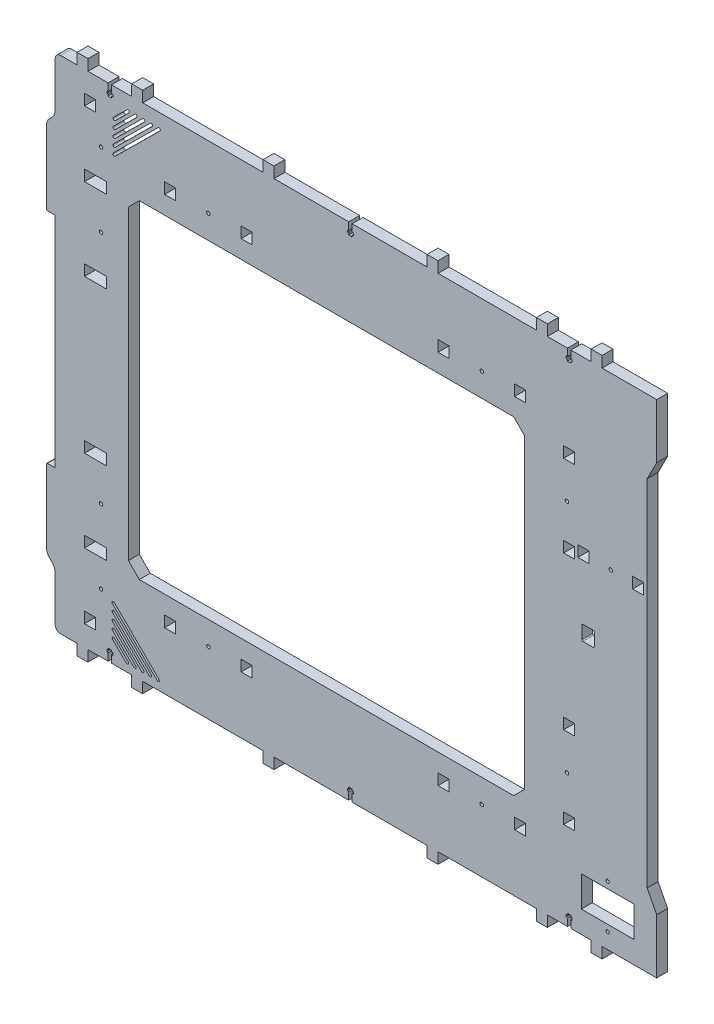
SolidWorks part; units mm, degrees
ref_plane "Front" through (0, 0, 0) normal (0, 0, 1) x (1, 0, 0)
ref_plane "Top" through (0, 0, 0) normal (0, 1, 0) x (1, 0, 0)
ref_plane "Right" through (0, 0, 0) normal (1, 0, 0) x (0, 0, -1)
sketch "Эскиз1" plane through (0, 0, 0) normal (0, 0, 1) x (1, 0, 0)
  line L256 (-788.0021, 303.5227) -> (-779.3021, 286.5227)
  line L257 (-788.0021, 627.5227) -> (-788.0021, 303.5227)
  line L258 (-779.3021, 644.5227) -> (-788.0021, 627.5227)
  line L259 (-779.3021, 694.5227) -> (-779.3021, 644.5227)
  line L260 (-829.2021, 694.5227) -> (-779.3021, 694.5227)
  line L261 (-829.2355, 704.5213) -> (-829.2021, 694.5227)
  line L262 (-839.2355, 704.5213) -> (-829.2355, 704.5213)
  line L263 (-839.4021, 694.5227) -> (-839.2355, 704.5213)
  line L264 (-857.7521, 694.5227) -> (-839.4021, 694.5227)
  line L265 (-857.7521, 687.7227) -> (-857.7521, 694.5227)
  line L266 (-856.5521, 687.7227) -> (-857.7521, 687.7227)
  line L267 (-856.5521, 685.5227) -> (-856.5521, 687.7227)
  line L268 (-857.7521, 685.5227) -> (-856.5521, 685.5227)
  line L269 (-857.7521, 684.0227) -> (-857.7521, 685.5227)
  line L270 (-860.8521, 684.0227) -> (-857.7521, 684.0227)
  line L271 (-860.8521, 685.5227) -> (-860.8521, 684.0227)
  line L272 (-862.0521, 685.5227) -> (-860.8521, 685.5227)
  line L273 (-862.0521, 687.7227) -> (-862.0521, 685.5227)
  line L274 (-860.8521, 687.7227) -> (-862.0521, 687.7227)
  line L275 (-860.8521, 694.5227) -> (-860.8521, 687.7227)
  line L276 (-879.2021, 694.5227) -> (-860.8521, 694.5227)
  line L277 (-879.2355, 704.5213) -> (-879.2021, 694.5227)
  line L278 (-889.2355, 704.5213) -> (-879.2355, 704.5213)
  line L279 (-889.4021, 694.5227) -> (-889.2355, 704.5213)
  line L280 (-979.2021, 694.5227) -> (-889.4021, 694.5227)
  line L281 (-979.2355, 704.5213) -> (-979.2021, 694.5227)
  line L282 (-989.2355, 704.5213) -> (-979.2355, 704.5213)
  line L283 (-989.4021, 694.5227) -> (-989.2355, 704.5213)
  line L284 (-1057.7521, 694.5227) -> (-989.4021, 694.5227)
  line L285 (-1057.7521, 687.7227) -> (-1057.7521, 694.5227)
  line L286 (-1056.5521, 687.7227) -> (-1057.7521, 687.7227)
  line L287 (-1056.5521, 685.5227) -> (-1056.5521, 687.7227)
  line L288 (-1057.7521, 685.5227) -> (-1056.5521, 685.5227)
  line L289 (-1057.7521, 684.0227) -> (-1057.7521, 685.5227)
  line L290 (-1060.8521, 684.0227) -> (-1057.7521, 684.0227)
  line L291 (-1060.8521, 685.5227) -> (-1060.8521, 684.0227)
  line L292 (-1062.0521, 685.5227) -> (-1060.8521, 685.5227)
  line L293 (-1062.0521, 687.7227) -> (-1062.0521, 685.5227)
  line L294 (-1060.8521, 687.7227) -> (-1062.0521, 687.7227)
  line L295 (-1060.8521, 694.5227) -> (-1060.8521, 687.7227)
  line L296 (-1129.2021, 694.5227) -> (-1060.8521, 694.5227)
  line L297 (-1129.2355, 704.5213) -> (-1129.2021, 694.5227)
  line L298 (-1139.2355, 704.5213) -> (-1129.2355, 704.5213)
  line L299 (-1139.4021, 694.5227) -> (-1139.2355, 704.5213)
  line L300 (-1249.2021, 694.5227) -> (-1139.4021, 694.5227)
  line L301 (-1249.2355, 704.5213) -> (-1249.2021, 694.5227)
  line L302 (-1259.2355, 704.5213) -> (-1249.2355, 704.5213)
  line L303 (-1259.4021, 694.5227) -> (-1259.2355, 704.5213)
  line L304 (-1277.7521, 694.5227) -> (-1259.4021, 694.5227)
  line L305 (-1277.7521, 687.7227) -> (-1277.7521, 694.5227)
  line L306 (-1276.5521, 687.7227) -> (-1277.7521, 687.7227)
  line L307 (-1276.5521, 685.5227) -> (-1276.5521, 687.7227)
  line L308 (-1277.7521, 685.5227) -> (-1276.5521, 685.5227)
  line L309 (-1277.7521, 684.0227) -> (-1277.7521, 685.5227)
  line L310 (-1280.8521, 684.0227) -> (-1277.7521, 684.0227)
  line L311 (-1280.8521, 685.5227) -> (-1280.8521, 684.0227)
  line L312 (-1282.0521, 685.5227) -> (-1280.8521, 685.5227)
  line L313 (-1282.0521, 687.7227) -> (-1282.0521, 685.5227)
  line L314 (-1280.8521, 687.7227) -> (-1282.0521, 687.7227)
  line L315 (-1280.8521, 694.5227) -> (-1280.8521, 687.7227)
  line L316 (-1299.2021, 694.5227) -> (-1280.8521, 694.5227)
  line L317 (-1299.2355, 704.5213) -> (-1299.2021, 694.5227)
  line L318 (-1309.2355, 704.5213) -> (-1299.2355, 704.5213)
  line L319 (-1309.4021, 694.5227) -> (-1309.2355, 704.5213)
  line L320 (-1324.3021, 694.5227) -> (-1309.4021, 694.5227)
  line L321 (-1329.3021, 648.6649) -> (-1329.3021, 689.5227)
  line L322 (-1334.3732, 639.4517) -> (-1332.231, 641.5938)
  line L323 (-1337.3021, 566.5227) -> (-1337.3021, 632.3806)
  line L324 (-1329.3021, 565.5227) -> (-1336.3021, 565.5227)
  line L325 (-1336.3021, 365.5227) -> (-1329.3021, 365.5227)
  line L326 (-1337.3021, 298.6649) -> (-1337.3021, 364.5227)
  line L327 (-1332.231, 289.4517) -> (-1334.3732, 291.5938)
  line L328 (-1329.3021, 241.5227) -> (-1329.3021, 282.3806)
  line L329 (-1309.4021, 236.5227) -> (-1324.3021, 236.5227)
  line L330 (-1309.3688, 226.5241) -> (-1309.4021, 236.5227)
  line L331 (-1299.3688, 226.5241) -> (-1309.3688, 226.5241)
  line L332 (-1299.2021, 236.5227) -> (-1299.3688, 226.5241)
  line L333 (-1280.8521, 236.5227) -> (-1299.2021, 236.5227)
  line L334 (-1280.8521, 243.3227) -> (-1280.8521, 236.5227)
  line L335 (-1282.0521, 243.3227) -> (-1280.8521, 243.3227)
  line L336 (-1282.0521, 245.5227) -> (-1282.0521, 243.3227)
  line L337 (-1280.8521, 245.5227) -> (-1282.0521, 245.5227)
  line L338 (-1280.8521, 247.0227) -> (-1280.8521, 245.5227)
  line L339 (-1277.7521, 247.0227) -> (-1280.8521, 247.0227)
  line L340 (-1277.7521, 245.5227) -> (-1277.7521, 247.0227)
  line L341 (-1276.5521, 245.5227) -> (-1277.7521, 245.5227)
  line L342 (-1276.5521, 243.3227) -> (-1276.5521, 245.5227)
  line L343 (-1277.7521, 243.3227) -> (-1276.5521, 243.3227)
  line L344 (-1277.7521, 236.5227) -> (-1277.7521, 243.3227)
  line L345 (-1259.4021, 236.5227) -> (-1277.7521, 236.5227)
  line L346 (-1259.3688, 226.5241) -> (-1259.4021, 236.5227)
  line L347 (-1249.3688, 226.5241) -> (-1259.3688, 226.5241)
  line L348 (-1249.2021, 236.5227) -> (-1249.3688, 226.5241)
  line L349 (-1139.4021, 236.5227) -> (-1249.2021, 236.5227)
  line L350 (-1139.2355, 226.5241) -> (-1139.4021, 236.5227)
  line L351 (-1129.2355, 226.5241) -> (-1139.2355, 226.5241)
  line L352 (-1129.2021, 236.5227) -> (-1129.2355, 226.5241)
  line L353 (-1060.8521, 236.5227) -> (-1129.2021, 236.5227)
  line L354 (-1060.8521, 243.3227) -> (-1060.8521, 236.5227)
  line L355 (-1062.0521, 243.3227) -> (-1060.8521, 243.3227)
  line L356 (-1062.0521, 245.5227) -> (-1062.0521, 243.3227)
  line L357 (-1060.8521, 245.5227) -> (-1062.0521, 245.5227)
  line L358 (-1060.8521, 247.0227) -> (-1060.8521, 245.5227)
  line L359 (-1057.7521, 247.0227) -> (-1060.8521, 247.0227)
  line L360 (-1057.7521, 245.5227) -> (-1057.7521, 247.0227)
  line L361 (-1056.5521, 245.5227) -> (-1057.7521, 245.5227)
  line L362 (-1056.5521, 243.3227) -> (-1056.5521, 245.5227)
  line L363 (-1057.7521, 243.3227) -> (-1056.5521, 243.3227)
  line L364 (-1057.7521, 236.5227) -> (-1057.7521, 243.3227)
  line L365 (-989.4021, 236.5227) -> (-1057.7521, 236.5227)
  line L366 (-989.2355, 226.5241) -> (-989.4021, 236.5227)
  line L367 (-979.2355, 226.5241) -> (-989.2355, 226.5241)
  line L368 (-979.2021, 236.5227) -> (-979.2355, 226.5241)
  line L369 (-889.4021, 236.5227) -> (-979.2021, 236.5227)
  line L370 (-889.2355, 226.5241) -> (-889.4021, 236.5227)
  line L371 (-879.2355, 226.5241) -> (-889.2355, 226.5241)
  line L372 (-879.2021, 236.5227) -> (-879.2355, 226.5241)
  line L373 (-860.8521, 236.5227) -> (-879.2021, 236.5227)
  line L374 (-860.8521, 243.3227) -> (-860.8521, 236.5227)
  line L375 (-862.0521, 243.3227) -> (-860.8521, 243.3227)
  line L376 (-862.0521, 245.5227) -> (-862.0521, 243.3227)
  line L377 (-860.8521, 245.5227) -> (-862.0521, 245.5227)
  line L378 (-860.8521, 247.0227) -> (-860.8521, 245.5227)
  line L379 (-857.7521, 247.0227) -> (-860.8521, 247.0227)
  line L380 (-857.7521, 245.5227) -> (-857.7521, 247.0227)
  line L381 (-856.5521, 245.5227) -> (-857.7521, 245.5227)
  line L382 (-856.5521, 243.3227) -> (-856.5521, 245.5227)
  line L383 (-857.7521, 243.3227) -> (-856.5521, 243.3227)
  line L384 (-857.7521, 236.5227) -> (-857.7521, 243.3227)
  line L385 (-839.4021, 236.5227) -> (-857.7521, 236.5227)
  line L386 (-839.2355, 226.5241) -> (-839.4021, 236.5227)
  line L387 (-829.2355, 226.5241) -> (-839.2355, 226.5241)
  line L388 (-829.2021, 236.5227) -> (-829.2355, 226.5241)
  line L389 (-779.3021, 236.5227) -> (-829.2021, 236.5227)
  line L390 (-779.3021, 286.5227) -> (-779.3021, 236.5227)
  line L391 (-1282.3021, 530.5227) -> (-1282.3021, 540.5227)
  line L392 (-1302.4021, 530.5227) -> (-1282.3021, 530.5227)
  line L393 (-1302.4021, 540.5227) -> (-1302.4021, 530.5227)
  line L394 (-1282.3021, 540.5227) -> (-1302.4021, 540.5227)
  line L395 (-1302.4021, 390.5227) -> (-1282.3021, 390.5227)
  line L396 (-1302.4021, 400.5227) -> (-1302.4021, 390.5227)
  line L397 (-1282.3021, 400.5227) -> (-1302.4021, 400.5227)
  line L398 (-1282.3021, 390.5227) -> (-1282.3021, 400.5227)
  line L399 (-1282.3021, 605.5227) -> (-1282.3021, 615.5227)
  line L400 (-1302.4021, 605.5227) -> (-1282.3021, 605.5227)
  line L401 (-1302.4021, 615.5227) -> (-1302.4021, 605.5227)
  line L402 (-1282.3021, 615.5227) -> (-1302.4021, 615.5227)
  line L403 (-1302.4021, 315.5227) -> (-1282.3021, 315.5227)
  line L404 (-1302.4021, 325.5227) -> (-1302.4021, 315.5227)
  line L405 (-1282.3021, 325.5227) -> (-1302.4021, 325.5227)
  line L406 (-1282.3021, 315.5227) -> (-1282.3021, 325.5227)
  line L407 (-1292.3021, 665.5227) -> (-1292.3021, 675.5227)
  line L408 (-1302.4021, 665.5227) -> (-1292.3021, 665.5227)
  line L409 (-1302.4021, 675.5227) -> (-1302.4021, 665.5227)
  line L410 (-1292.3021, 675.5227) -> (-1302.4021, 675.5227)
  line L411 (-1302.4021, 255.5227) -> (-1292.3021, 255.5227)
  line L412 (-1302.4021, 265.5227) -> (-1302.4021, 255.5227)
  line L413 (-1292.3021, 265.5227) -> (-1302.4021, 265.5227)
  line L414 (-1292.3021, 255.5227) -> (-1292.3021, 265.5227)
  line L415 (-854.2998, 530.5227) -> (-854.2998, 540.5227)
  line L416 (-864.3998, 530.5227) -> (-854.2998, 530.5227)
  line L417 (-864.3998, 540.5227) -> (-864.3998, 530.5227)
  line L418 (-854.2998, 540.5227) -> (-864.3998, 540.5227)
  line L419 (-864.3998, 390.5227) -> (-854.2998, 390.5227)
  line L420 (-864.3998, 400.5227) -> (-864.3998, 390.5227)
  line L421 (-854.2998, 400.5227) -> (-864.3998, 400.5227)
  line L422 (-854.2998, 390.5227) -> (-854.2998, 400.5227)
  line L423 (-864.3998, 315.5227) -> (-854.2998, 315.5227)
  line L424 (-864.3998, 325.5227) -> (-864.3998, 315.5227)
  line L425 (-854.2998, 325.5227) -> (-864.3998, 325.5227)
  line L426 (-854.2998, 315.5227) -> (-854.2998, 325.5227)
  line L427 (-854.2998, 605.5227) -> (-854.2998, 615.5227)
  line L428 (-864.3998, 605.5227) -> (-854.2998, 605.5227)
  line L429 (-864.3998, 615.5227) -> (-864.3998, 605.5227)
  line L430 (-854.2998, 615.5227) -> (-864.3998, 615.5227)
  line L431 (-1329.3021, 365.5227) -> (-1329.3021, 565.5227)
  line L432 (-800.1725, 256.6732) -> (-800.1725, 284.6732)
  line L433 (-800.1725, 284.6732) -> (-848.1725, 284.6732)
  line L434 (-848.1725, 284.6732) -> (-848.1725, 256.6732)
  line L435 (-848.1725, 256.6732) -> (-800.1725, 256.6732)
  line L436 (-1219.2021, 288.9227) -> (-1219.2021, 299.0227)
  line L437 (-1219.2021, 299.0227) -> (-1229.2021, 299.0227)
  line L438 (-1229.2021, 299.0227) -> (-1229.2021, 288.9227)
  line L439 (-1229.2021, 288.9227) -> (-1219.2021, 288.9227)
  line L440 (-899.2021, 288.9227) -> (-899.2021, 299.0227)
  line L441 (-899.2021, 299.0227) -> (-909.2021, 299.0227)
  line L442 (-909.2021, 299.0227) -> (-909.2021, 288.9227)
  line L443 (-909.2021, 288.9227) -> (-899.2021, 288.9227)
  line L444 (-1149.2021, 288.9227) -> (-1149.2021, 299.0227)
  line L445 (-1149.2021, 299.0227) -> (-1159.2021, 299.0227)
  line L446 (-1159.2021, 299.0227) -> (-1159.2021, 288.9227)
  line L447 (-1159.2021, 288.9227) -> (-1149.2021, 288.9227)
  line L448 (-969.2021, 288.9227) -> (-969.2021, 299.0227)
  line L449 (-969.2021, 299.0227) -> (-979.2021, 299.0227)
  line L450 (-979.2021, 299.0227) -> (-979.2021, 288.9227)
  line L451 (-979.2021, 288.9227) -> (-969.2021, 288.9227)
  line L452 (-1219.2021, 632.0227) -> (-1219.2021, 642.1227)
  line L453 (-1219.2021, 642.1227) -> (-1229.2021, 642.1227)
  line L454 (-1229.2021, 642.1227) -> (-1229.2021, 632.0227)
  line L455 (-1229.2021, 632.0227) -> (-1219.2021, 632.0227)
  line L456 (-899.2021, 632.0227) -> (-899.2021, 642.1227)
  line L457 (-899.2021, 642.1227) -> (-909.2021, 642.1227)
  line L458 (-909.2021, 642.1227) -> (-909.2021, 632.0227)
  line L459 (-909.2021, 632.0227) -> (-899.2021, 632.0227)
  line L460 (-1149.2021, 632.0227) -> (-1149.2021, 642.1227)
  line L461 (-1149.2021, 642.1227) -> (-1159.2021, 642.1227)
  line L462 (-1159.2021, 642.1227) -> (-1159.2021, 632.0227)
  line L463 (-1159.2021, 632.0227) -> (-1149.2021, 632.0227)
  line L464 (-969.2021, 632.0227) -> (-969.2021, 642.1227)
  line L465 (-969.2021, 642.1227) -> (-979.2021, 642.1227)
  line L466 (-979.2021, 642.1227) -> (-979.2021, 632.0227)
  line L467 (-979.2021, 632.0227) -> (-969.2021, 632.0227)
  line L468 (-1257.2892, 243.5969) -> (-1276.8417, 262.9346)
  line L469 (-1275.0838, 264.7121) -> (-1255.5312, 245.3744)
  line L470 (-1250.2182, 243.6359) -> (-1276.8808, 270.0055)
  line L471 (-1275.1228, 271.783) -> (-1248.4602, 245.4134)
  line L472 (-1243.1472, 243.675) -> (-1276.9199, 277.0765)
  line L473 (-1275.1619, 278.854) -> (-1241.3893, 245.4525)
  line L474 (-1264.3601, 243.5578) -> (-1276.8027, 255.8636)
  line L475 (-1275.0447, 257.6411) -> (-1262.6021, 245.3353)
  line L476 (-1236.0763, 243.7141) -> (-1276.9589, 284.1474)
  line L477 (-1275.201, 285.925) -> (-1234.3183, 245.4916)
  line L478 (-1256.453, 681.9744) -> (-1276.0056, 662.6367)
  line L479 (-1274.2476, 660.8592) -> (-1254.695, 680.1969)
  line L480 (-1249.382, 681.9354) -> (-1276.0446, 655.5658)
  line L481 (-1274.2867, 653.7882) -> (-1247.6241, 680.1578)
  line L482 (-1242.3111, 681.8963) -> (-1276.0837, 648.4948)
  line L483 (-1274.3257, 646.7173) -> (-1240.5531, 680.1188)
  line L484 (-1263.5239, 682.0135) -> (-1275.9665, 669.7077)
  line L485 (-1274.2085, 667.9302) -> (-1261.766, 680.236)
  line L486 (-1235.2401, 681.8572) -> (-1276.1228, 641.4238)
  line L487 (-1274.3648, 639.6463) -> (-1233.4821, 680.0797)
  line L492 (-846.7998, 469.3227) -> (-837.2998, 469.3227)
  line L493 (-836.2998, 470.3227) -> (-836.2998, 481.8227)
  line L494 (-837.2998, 482.8227) -> (-846.7998, 482.8227)
  line L495 (-847.7998, 481.8227) -> (-847.7998, 470.3227)
  line L496 (-1262.3021, 325.5227) -> (-1262.3021, 605.5227)
  line L497 (-1252.3021, 615.5227) -> (-910.0873, 615.5227)
  line L498 (-900.0873, 605.5227) -> (-900.0873, 325.5227)
  line L499 (-910.0873, 315.5227) -> (-1252.3021, 315.5227)
  line L500 (-1252.3021, 615.5227) -> (-1262.3021, 605.5227)
  line L501 (-1262.3021, 325.5227) -> (-1252.3021, 315.5227)
  line L502 (-910.0873, 315.5227) -> (-900.0873, 325.5227)
  line L503 (-910.0873, 615.5227) -> (-900.0873, 605.5227)
  line L504 (-841.2998, 543.6941) -> (-851.2998, 543.6941)
  line L505 (-851.2998, 543.6941) -> (-851.2998, 533.5941)
  line L506 (-851.2998, 533.5941) -> (-841.2998, 533.5941)
  line L507 (-841.2998, 533.5941) -> (-841.2998, 543.6941)
  line L508 (-791.2998, 543.6941) -> (-801.2998, 543.6941)
  line L509 (-801.2998, 543.6941) -> (-801.2998, 533.5941)
  line L510 (-801.2998, 533.5941) -> (-791.2998, 533.5941)
  line L511 (-791.2998, 533.5941) -> (-791.2998, 543.6941)
  arc A91 (-1324.3021, 694.5227) -> (-1329.3021, 689.5227) centre (-1324.3021, 689.5227) ccw
  arc A92 (-1332.231, 641.5938) -> (-1329.3021, 648.6649) centre (-1339.3021, 648.6649) ccw
  arc A93 (-1334.3732, 639.4517) -> (-1337.3021, 632.3806) centre (-1327.3021, 632.3806) ccw
  arc A94 (-1337.3021, 566.5227) -> (-1336.3021, 565.5227) centre (-1336.3021, 566.5227) ccw
  arc A95 (-1336.3021, 365.5227) -> (-1337.3021, 364.5227) centre (-1336.3021, 364.5227) ccw
  arc A96 (-1337.3021, 298.6649) -> (-1334.3732, 291.5938) centre (-1327.3021, 298.6649) ccw
  arc A97 (-1329.3021, 282.3806) -> (-1332.231, 289.4517) centre (-1339.3021, 282.3806) ccw
  arc A98 (-1329.3021, 241.5227) -> (-1324.3021, 236.5227) centre (-1324.3021, 241.5227) ccw
  circle A99 centre (-1287.3521, 358.0227) radius 1.6
  circle A100 centre (-861.3498, 358.0227) radius 1.6
  circle A101 centre (-1287.3521, 573.0227) radius 1.6
  circle A102 centre (-861.3498, 573.0227) radius 1.6
  circle A103 centre (-1287.3521, 290.5227) radius 1.6
  circle A104 centre (-1287.3521, 640.5227) radius 1.6
  circle A114 centre (-824.1725, 290.6732) radius 1.55
  circle A115 centre (-824.1725, 250.6732) radius 1.55
  circle A122 centre (-1189.2021, 293.9727) radius 1.6
  circle A123 centre (-939.2021, 293.9727) radius 1.6
  circle A124 centre (-1189.2021, 637.0727) radius 1.6
  circle A125 centre (-939.2021, 637.0727) radius 1.6
  arc A126 (-1257.2892, 243.5969) -> (-1255.5312, 245.3744) centre (-1256.4102, 244.4856) ccw
  arc A127 (-1275.0838, 264.7121) -> (-1276.8417, 262.9346) centre (-1275.9627, 263.8233) ccw
  arc A128 (-1250.2182, 243.6359) -> (-1248.4602, 245.4134) centre (-1249.3392, 244.5247) ccw
  arc A129 (-1275.1228, 271.783) -> (-1276.8808, 270.0055) centre (-1276.0018, 270.8943) ccw
  arc A130 (-1243.1472, 243.675) -> (-1241.3893, 245.4525) centre (-1242.2682, 244.5637) ccw
  arc A131 (-1275.1619, 278.854) -> (-1276.9199, 277.0765) centre (-1276.0409, 277.9652) ccw
  arc A132 (-1264.3601, 243.5578) -> (-1262.6021, 245.3353) centre (-1263.4811, 244.4465) ccw
  arc A133 (-1275.0447, 257.6411) -> (-1276.8027, 255.8636) centre (-1275.9237, 256.7524) ccw
  arc A134 (-1236.0763, 243.7141) -> (-1234.3183, 245.4916) centre (-1235.1973, 244.6028) ccw
  arc A135 (-1275.201, 285.925) -> (-1276.9589, 284.1474) centre (-1276.0799, 285.0362) ccw
  arc A136 (-1254.695, 680.1969) -> (-1256.453, 681.9744) centre (-1255.574, 681.0857) ccw
  arc A137 (-1276.0056, 662.6367) -> (-1274.2476, 660.8592) centre (-1275.1266, 661.748) ccw
  arc A138 (-1247.6241, 680.1578) -> (-1249.382, 681.9354) centre (-1248.503, 681.0466) ccw
  arc A139 (-1276.0446, 655.5658) -> (-1274.2867, 653.7882) centre (-1275.1656, 654.677) ccw
  arc A140 (-1240.5531, 680.1188) -> (-1242.3111, 681.8963) centre (-1241.4321, 681.0075) ccw
  arc A141 (-1276.0837, 648.4948) -> (-1274.3257, 646.7173) centre (-1275.2047, 647.606) ccw
  arc A142 (-1261.766, 680.236) -> (-1263.5239, 682.0135) centre (-1262.645, 681.1247) ccw
  arc A143 (-1275.9665, 669.7077) -> (-1274.2085, 667.9302) centre (-1275.0875, 668.8189) ccw
  arc A144 (-1233.4821, 680.0797) -> (-1235.2401, 681.8572) centre (-1234.3611, 680.9685) ccw
  arc A145 (-1276.1228, 641.4238) -> (-1274.3648, 639.6463) centre (-1275.2438, 640.5351) ccw
  arc A177 (-837.2998, 469.3227) -> (-836.2998, 470.3227) centre (-837.2998, 470.3227) ccw
  arc A178 (-847.7998, 470.3227) -> (-846.7998, 469.3227) centre (-846.7998, 470.3227) ccw
  arc A179 (-836.2998, 481.8227) -> (-837.2998, 482.8227) centre (-837.2998, 481.8227) ccw
  arc A180 (-846.7998, 482.8227) -> (-847.7998, 481.8227) centre (-846.7998, 481.8227) ccw
  circle A181 centre (-821.2998, 538.6441) radius 1.6
  point P360 (-1302.6746, 675.5227)
  point P365 (-1285.3391, 255.5227)
  point P434 (0, 0)
  point P437 (-1285.0145, 265.5227)
  point P439 (-1302.7293, 665.5227)
extrude "Бобышка-Вытянуть1" add sketch "Эскиз1" along normal blind 10
